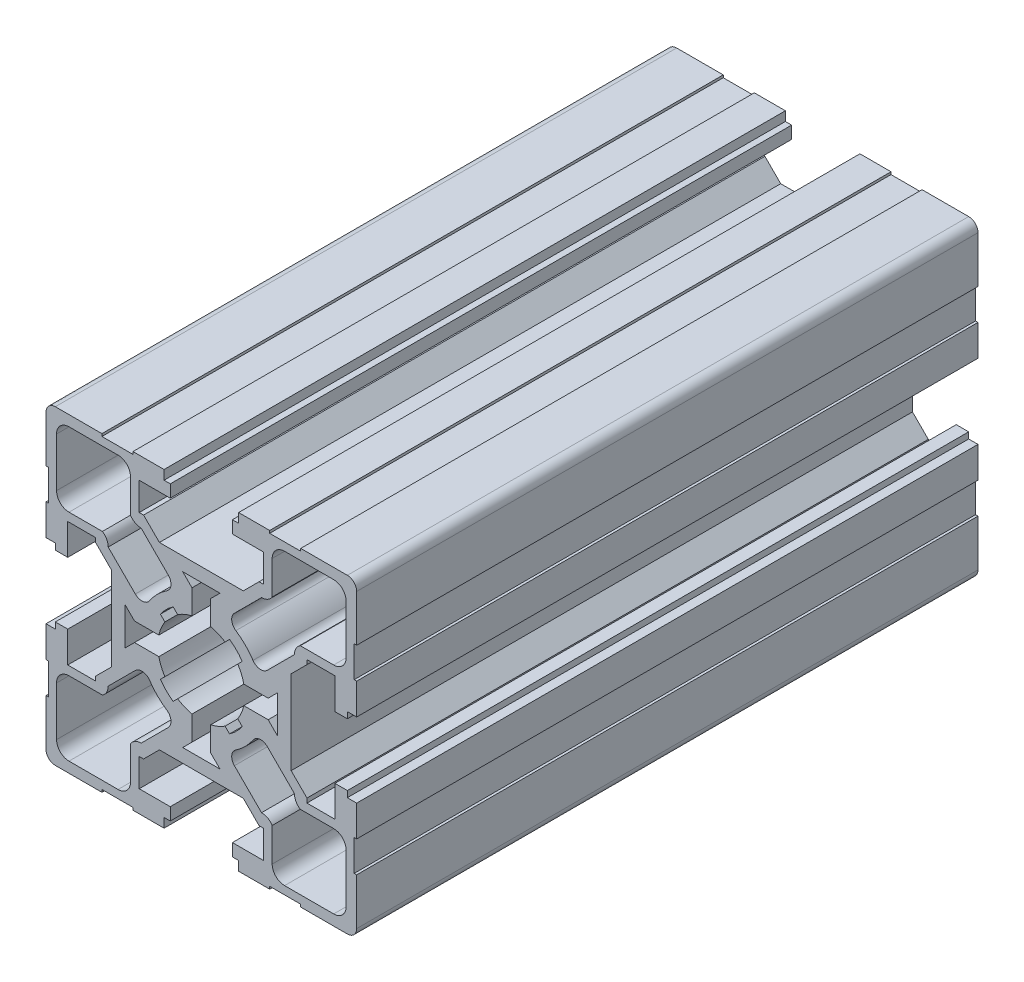
SolidWorks part; units mm, degrees
ref_plane "前视基准面" through (0, 0, 0) normal (0, 0, 1) x (1, 0, 0)
ref_plane "上视基准面" through (0, 0, 0) normal (0, 1, 0) x (1, 0, 0)
ref_plane "右视基准面" through (0, 0, 0) normal (1, 0, 0) x (0, 0, -1)
sketch "草图1" plane through (0, 0, 0) normal (0, 0, 1) x (1, 0, 0)
  line L0 (-5.8772, 24.5458) -> (-10.8772, 24.5458)
  line L1 (-15.8772, 24.5458) -> (-23.3772, 24.5458)
  line L2 (-24.8772, 23.0458) -> (-24.8772, 15.5458)
  line L3 (-24.8772, 10.5458) -> (-24.8772, 5.5458)
  line L4 (-10.8772, 24.1458) -> (-15.8772, 24.1458)
  line L5 (-11.2772, 15.4704) -> (-11.2772, 20.8458)
  line L6 (-13.2772, 22.8458) -> (-21.1772, 22.8458)
  line L7 (-23.1772, 20.8458) -> (-23.1772, 12.9458)
  line L8 (-21.1772, 10.9458) -> (-15.8018, 10.9458)
  line L9 (-4.8772, 21.0458) -> (-9.8772, 21.0458)
  line L10 (-21.3772, 9.5458) -> (-21.3772, 4.5458)
  line L11 (-9.173, 16.5458) -> (-9.8772, 16.5458)
  line L12 (-16.8772, 9.5458) -> (-16.8772, 8.8416)
  line L13 (-4.8772, 23.0458) -> (-5.8772, 23.0458)
  line L14 (-23.3772, 5.5458) -> (-23.3772, 4.5458)
  line L15 (-21.3772, 9.5458) -> (-16.8772, 9.5458)
  line L16 (-24.8772, 5.5458) -> (-23.3772, 5.5458)
  line L17 (-23.3772, 4.5458) -> (-21.3772, 4.5458)
  line L18 (-10.8772, 24.5458) -> (-10.8772, 24.1458)
  line L19 (-15.8772, 24.5458) -> (-15.8772, 24.1458)
  line L20 (-9.8772, 21.0458) -> (-9.8772, 16.5458)
  line L21 (-5.8772, 24.5458) -> (-5.8772, 23.0458)
  line L22 (-4.8772, 23.0458) -> (-4.8772, 21.0458)
  line L23 (-5.7449, 3.3629) -> (-6.4657, 4.0836)
  line L24 (-3.6943, 5.4135) -> (-4.4151, 6.1343)
  line L25 (5.9905, 3.3629) -> (6.7113, 4.0836)
  line L26 (3.9399, 5.4135) -> (4.6607, 6.1343)
  line L27 (-5.7449, -4.2713) -> (-6.4657, -4.9921)
  line L28 (-3.6943, -6.3219) -> (-4.4151, -7.0427)
  line L29 (5.9905, -4.2713) -> (6.7113, -4.9921)
  line L30 (3.9399, -6.3219) -> (4.6607, -7.0427)
  line L31 (-5.2021, 10.1707) -> (-9.5689, 14.5375)
  line L32 (-6.6272, 14) -> (-9.173, 16.5458)
  line L34 (-10.5021, 4.8707) -> (-14.8689, 9.2375)
  line L35 (-14.3314, 6.2958) -> (-16.8772, 8.8416)
  line L36 (-6.6272, 14) -> (0.1228, 14)
  line L37 (-14.3314, 6.2958) -> (-14.3314, -0.4542)
  line L38 (-10.6327, 1.0458) -> (-12.1327, 2.5458)
  line L39 (-12.1327, 2.5458) -> (-12.1327, -0.4542)
  line L40 (-10.6327, 1.0458) -> (-6.7146, 1.0458)
  line L41 (-1.3772, 10.3013) -> (-2.8772, 11.8013)
  line L42 (-2.8772, 11.8013) -> (0.1228, 11.8013)
  line L43 (-1.3772, 10.3013) -> (-1.3772, 6.3832)
  line L44 (-24.4772, 10.5458) -> (-24.4772, 15.5458)
  line L45 (-24.8772, 10.5458) -> (-24.4772, 10.5458)
  line L46 (-24.8772, 15.5458) -> (-24.4772, 15.5458)
  line L47 (6.1228, 24.5458) -> (11.1228, 24.5458)
  line L48 (16.1228, 24.5458) -> (23.6228, 24.5458)
  line L49 (25.1228, 23.0458) -> (25.1228, 15.5458)
  line L50 (25.1228, 10.5458) -> (25.1228, 5.5458)
  line L51 (11.1228, 24.1458) -> (16.1228, 24.1458)
  line L52 (11.5228, 15.4704) -> (11.5228, 20.8458)
  line L53 (13.5228, 22.8458) -> (21.4228, 22.8458)
  line L54 (23.4228, 20.8458) -> (23.4228, 12.9458)
  line L55 (21.4228, 10.9458) -> (16.0474, 10.9458)
  line L56 (5.1228, 21.0458) -> (10.1228, 21.0458)
  line L57 (21.6228, 9.5458) -> (21.6228, 4.5458)
  line L58 (9.4186, 16.5458) -> (10.1228, 16.5458)
  line L59 (17.1228, 9.5458) -> (17.1228, 8.8416)
  line L60 (5.1228, 23.0458) -> (6.1228, 23.0458)
  line L61 (23.6228, 5.5458) -> (23.6228, 4.5458)
  line L62 (21.6228, 9.5458) -> (17.1228, 9.5458)
  line L63 (25.1228, 5.5458) -> (23.6228, 5.5458)
  line L64 (23.6228, 4.5458) -> (21.6228, 4.5458)
  line L65 (11.1228, 24.5458) -> (11.1228, 24.1458)
  line L66 (16.1228, 24.5458) -> (16.1228, 24.1458)
  line L67 (10.1228, 21.0458) -> (10.1228, 16.5458)
  line L68 (6.1228, 24.5458) -> (6.1228, 23.0458)
  line L69 (5.4477, 10.1707) -> (9.8145, 14.5375)
  line L70 (6.8728, 14) -> (9.4186, 16.5458)
  line L72 (10.7477, 4.8707) -> (15.1145, 9.2375)
  line L73 (14.577, 6.2958) -> (17.1228, 8.8416)
  line L74 (6.8728, 14) -> (0.1228, 14)
  line L75 (14.577, 6.2958) -> (14.577, -0.4542)
  line L76 (10.8783, 1.0458) -> (12.3783, 2.5458)
  line L77 (12.3783, 2.5458) -> (12.3783, -0.4542)
  line L78 (10.8783, 1.0458) -> (6.9602, 1.0458)
  line L79 (1.6228, 10.3013) -> (3.1228, 11.8013)
  line L80 (3.1228, 11.8013) -> (0.1228, 11.8013)
  line L81 (1.6228, 10.3013) -> (1.6228, 6.3832)
  line L82 (24.7228, 10.5458) -> (24.7228, 15.5458)
  line L83 (25.1228, 10.5458) -> (24.7228, 10.5458)
  line L84 (25.1228, 15.5458) -> (24.7228, 15.5458)
  line L85 (5.1228, 23.0458) -> (5.1228, 21.0458)
  line L86 (-5.8772, -25.4542) -> (-10.8772, -25.4542)
  line L87 (-15.8772, -25.4542) -> (-23.3772, -25.4542)
  line L88 (-24.8772, -23.9542) -> (-24.8772, -16.4542)
  line L89 (-24.8772, -11.4542) -> (-24.8772, -6.4542)
  line L90 (-10.8772, -25.0542) -> (-15.8772, -25.0542)
  line L91 (-11.2772, -16.3788) -> (-11.2772, -21.7542)
  line L92 (-13.2772, -23.7542) -> (-21.1772, -23.7542)
  line L93 (-23.1772, -21.7542) -> (-23.1772, -13.8542)
  line L94 (-21.1772, -11.8542) -> (-15.8018, -11.8542)
  line L95 (-4.8772, -21.9542) -> (-9.8772, -21.9542)
  line L96 (-21.3772, -10.4542) -> (-21.3772, -5.4542)
  line L97 (-9.173, -17.4542) -> (-9.8772, -17.4542)
  line L98 (-16.8772, -10.4542) -> (-16.8772, -9.75)
  line L99 (-4.8772, -23.9542) -> (-5.8772, -23.9542)
  line L100 (-23.3772, -6.4542) -> (-23.3772, -5.4542)
  line L101 (-21.3772, -10.4542) -> (-16.8772, -10.4542)
  line L102 (-24.8772, -6.4542) -> (-23.3772, -6.4542)
  line L103 (-23.3772, -5.4542) -> (-21.3772, -5.4542)
  line L104 (-10.8772, -25.4542) -> (-10.8772, -25.0542)
  line L105 (-15.8772, -25.4542) -> (-15.8772, -25.0542)
  line L106 (-9.8772, -21.9542) -> (-9.8772, -17.4542)
  line L107 (-5.8772, -25.4542) -> (-5.8772, -23.9542)
  line L108 (-4.8772, -23.9542) -> (-4.8772, -21.9542)
  line L109 (-5.2021, -11.0791) -> (-9.5689, -15.4459)
  line L110 (-6.6272, -14.9084) -> (-9.173, -17.4542)
  line L112 (-10.5021, -5.7791) -> (-14.8689, -10.1459)
  line L113 (-14.3314, -7.2042) -> (-16.8772, -9.75)
  line L114 (-6.6272, -14.9084) -> (0.1228, -14.9084)
  line L115 (-14.3314, -7.2042) -> (-14.3314, -0.4542)
  line L116 (-10.6327, -1.9542) -> (-12.1327, -3.4542)
  line L117 (-12.1327, -3.4542) -> (-12.1327, -0.4542)
  line L118 (-10.6327, -1.9542) -> (-6.7146, -1.9542)
  line L119 (-1.3772, -11.2097) -> (-2.8772, -12.7097)
  line L120 (-2.8772, -12.7097) -> (0.1228, -12.7097)
  line L121 (-1.3772, -11.2097) -> (-1.3772, -7.2916)
  line L122 (-24.4772, -11.4542) -> (-24.4772, -16.4542)
  line L123 (-24.8772, -11.4542) -> (-24.4772, -11.4542)
  line L124 (-24.8772, -16.4542) -> (-24.4772, -16.4542)
  line L125 (6.1228, -25.4542) -> (11.1228, -25.4542)
  line L126 (16.1228, -25.4542) -> (23.6228, -25.4542)
  line L127 (25.1228, -23.9542) -> (25.1228, -16.4542)
  line L128 (25.1228, -11.4542) -> (25.1228, -6.4542)
  line L129 (11.1228, -25.0542) -> (16.1228, -25.0542)
  line L130 (11.5228, -16.3788) -> (11.5228, -21.7542)
  line L131 (13.5228, -23.7542) -> (21.4228, -23.7542)
  line L132 (23.4228, -21.7542) -> (23.4228, -13.8542)
  line L133 (21.4228, -11.8542) -> (16.0474, -11.8542)
  line L134 (5.1228, -21.9542) -> (10.1228, -21.9542)
  line L135 (21.6228, -10.4542) -> (21.6228, -5.4542)
  line L136 (9.4186, -17.4542) -> (10.1228, -17.4542)
  line L137 (17.1228, -10.4542) -> (17.1228, -9.75)
  line L138 (5.1228, -23.9542) -> (6.1228, -23.9542)
  line L139 (23.6228, -6.4542) -> (23.6228, -5.4542)
  line L140 (21.6228, -10.4542) -> (17.1228, -10.4542)
  line L141 (25.1228, -6.4542) -> (23.6228, -6.4542)
  line L142 (23.6228, -5.4542) -> (21.6228, -5.4542)
  line L143 (11.1228, -25.4542) -> (11.1228, -25.0542)
  line L144 (16.1228, -25.4542) -> (16.1228, -25.0542)
  line L145 (10.1228, -21.9542) -> (10.1228, -17.4542)
  line L146 (6.1228, -25.4542) -> (6.1228, -23.9542)
  line L147 (5.4477, -11.0791) -> (9.8145, -15.4459)
  line L148 (6.8728, -14.9084) -> (9.4186, -17.4542)
  line L150 (10.7477, -5.7791) -> (15.1145, -10.1459)
  line L151 (14.577, -7.2042) -> (17.1228, -9.75)
  line L152 (6.8728, -14.9084) -> (0.1228, -14.9084)
  line L153 (14.577, -7.2042) -> (14.577, -0.4542)
  line L154 (10.8783, -1.9542) -> (12.3783, -3.4542)
  line L155 (12.3783, -3.4542) -> (12.3783, -0.4542)
  line L156 (10.8783, -1.9542) -> (6.9602, -1.9542)
  line L157 (1.6228, -11.2097) -> (3.1228, -12.7097)
  line L158 (3.1228, -12.7097) -> (0.1228, -12.7097)
  line L159 (1.6228, -11.2097) -> (1.6228, -7.2916)
  line L160 (24.7228, -11.4542) -> (24.7228, -16.4542)
  line L161 (25.1228, -11.4542) -> (24.7228, -11.4542)
  line L162 (25.1228, -16.4542) -> (24.7228, -16.4542)
  line L163 (5.1228, -23.9542) -> (5.1228, -21.9542)
  arc A0 (-23.3772, 24.5458) -> (-24.8772, 23.0458) centre (-23.3772, 23.0458) ccw
  arc A1 (-11.2772, 20.8458) -> (-13.2772, 22.8458) centre (-13.2772, 20.8458) ccw
  arc A2 (-21.1772, 22.8458) -> (-23.1772, 20.8458) centre (-21.1772, 20.8458) ccw
  arc A3 (-23.1772, 12.9458) -> (-21.1772, 10.9458) centre (-21.1772, 12.9458) ccw
  arc A4 (-5.7449, 3.3629) -> (-6.7146, 1.0458) centre (0.1228, -0.4542) ccw
  arc A5 (-6.7146, -1.9542) -> (-5.7449, -4.2713) centre (0.1228, -0.4542) ccw
  arc A6 (-3.6943, -6.3219) -> (-1.3772, -7.2916) centre (0.1228, -0.4542) ccw
  arc A7 (1.6228, -7.2916) -> (3.9399, -6.3219) centre (0.1228, -0.4542) ccw
  arc A8 (5.9905, -4.2713) -> (6.9602, -1.9542) centre (0.1228, -0.4542) ccw
  arc A9 (6.9602, 1.0458) -> (5.9905, 3.3629) centre (0.1228, -0.4542) ccw
  arc A10 (3.9399, 5.4135) -> (1.6228, 6.3832) centre (0.1228, -0.4542) ccw
  arc A11 (-1.3772, 6.3832) -> (-3.6943, 5.4135) centre (0.1228, -0.4542) ccw
  arc A12 (-4.4151, 6.1343) -> (-6.4657, 4.0836) centre (0.1228, -0.4542) ccw
  arc A13 (-5.4299, 7.8625) -> (-8.1939, 5.0985) centre (0.1228, -0.4542) ccw
  arc A14 (-5.4299, 7.8625) -> (-5.2021, 10.1707) centre (-6.2628, 9.11) ccw
  arc A15 (-10.5021, 4.8707) -> (-8.1939, 5.0985) centre (-9.4414, 5.9314) ccw
  arc A16 (6.7113, 4.0836) -> (4.6607, 6.1343) centre (0.1228, -0.4542) ccw
  arc A17 (-6.4657, -4.9921) -> (-4.4151, -7.0427) centre (0.1228, -0.4542) ccw
  arc A18 (4.6607, -7.0427) -> (6.7113, -4.9921) centre (0.1228, -0.4542) ccw
  arc A19 (-11.2772, 15.4704) -> (-9.5689, 14.5375) centre (-9.5856, 16.5374) ccw
  arc A20 (-14.8689, 9.2375) -> (-15.8018, 10.9458) centre (-16.8688, 9.2542) ccw
  arc A21 (25.1228, 23.0458) -> (23.6228, 24.5458) centre (23.6228, 23.0458) ccw
  arc A22 (13.5228, 22.8458) -> (11.5228, 20.8458) centre (13.5228, 20.8458) ccw
  arc A23 (23.4228, 20.8458) -> (21.4228, 22.8458) centre (21.4228, 20.8458) ccw
  arc A24 (21.4228, 10.9458) -> (23.4228, 12.9458) centre (21.4228, 12.9458) ccw
  arc A25 (8.4395, 5.0985) -> (5.6755, 7.8625) centre (0.1228, -0.4542) ccw
  arc A26 (5.4477, 10.1707) -> (5.6755, 7.8625) centre (6.5084, 9.11) ccw
  arc A27 (8.4395, 5.0985) -> (10.7477, 4.8707) centre (9.687, 5.9314) ccw
  arc A28 (9.8145, 14.5375) -> (11.5228, 15.4704) centre (9.8312, 16.5374) ccw
  arc A29 (16.0474, 10.9458) -> (15.1145, 9.2375) centre (17.1144, 9.2542) ccw
  arc A30 (-24.8772, -23.9542) -> (-23.3772, -25.4542) centre (-23.3772, -23.9542) ccw
  arc A31 (-13.2772, -23.7542) -> (-11.2772, -21.7542) centre (-13.2772, -21.7542) ccw
  arc A32 (-23.1772, -21.7542) -> (-21.1772, -23.7542) centre (-21.1772, -21.7542) ccw
  arc A33 (-21.1772, -11.8542) -> (-23.1772, -13.8542) centre (-21.1772, -13.8542) ccw
  arc A34 (-8.1939, -6.0069) -> (-5.4299, -8.7709) centre (0.1228, -0.4542) ccw
  arc A35 (-5.2021, -11.0791) -> (-5.4299, -8.7709) centre (-6.2628, -10.0184) ccw
  arc A36 (-8.1939, -6.0069) -> (-10.5021, -5.7791) centre (-9.4414, -6.8398) ccw
  arc A37 (-9.5689, -15.4459) -> (-11.2772, -16.3788) centre (-9.5856, -17.4458) ccw
  arc A38 (-15.8018, -11.8542) -> (-14.8689, -10.1459) centre (-16.8688, -10.1626) ccw
  arc A39 (23.6228, -25.4542) -> (25.1228, -23.9542) centre (23.6228, -23.9542) ccw
  arc A40 (11.5228, -21.7542) -> (13.5228, -23.7542) centre (13.5228, -21.7542) ccw
  arc A41 (21.4228, -23.7542) -> (23.4228, -21.7542) centre (21.4228, -21.7542) ccw
  arc A42 (23.4228, -13.8542) -> (21.4228, -11.8542) centre (21.4228, -13.8542) ccw
  arc A43 (5.6755, -8.7709) -> (8.4395, -6.0069) centre (0.1228, -0.4542) ccw
  arc A44 (5.6755, -8.7709) -> (5.4477, -11.0791) centre (6.5084, -10.0184) ccw
  arc A45 (10.7477, -5.7791) -> (8.4395, -6.0069) centre (9.687, -6.8398) ccw
  arc A46 (11.5228, -16.3788) -> (9.8145, -15.4459) centre (9.8312, -17.4458) ccw
  arc A47 (15.1145, -10.1459) -> (16.0474, -11.8542) centre (17.1144, -10.1626) ccw
extrude "凸台-拉伸1" add sketch "草图1" along normal blind 100
